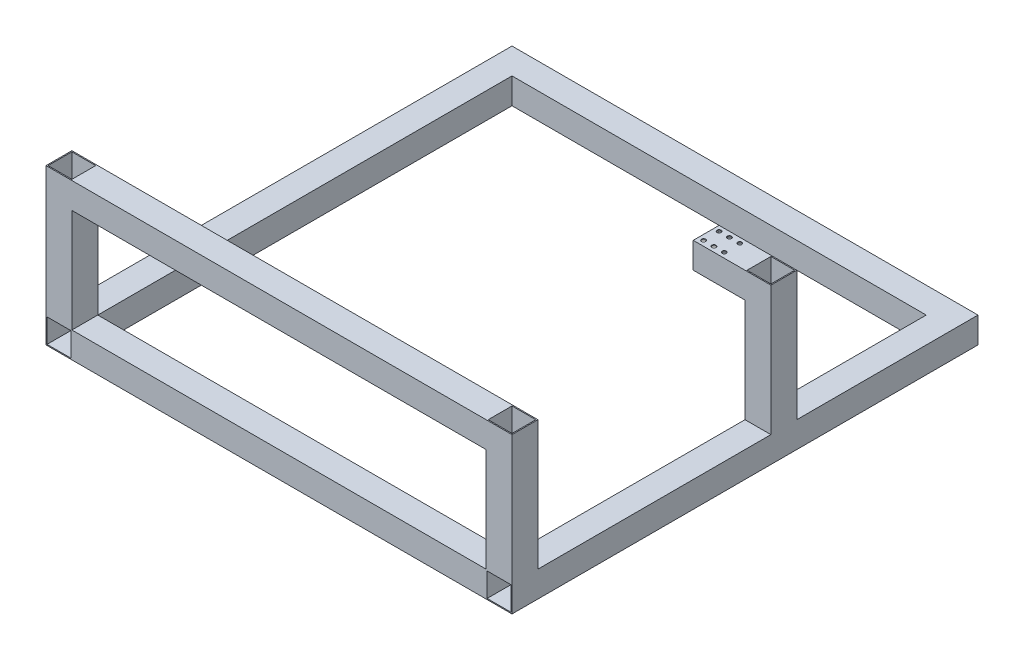
SolidWorks part; units mm, degrees
ref_plane "Front Plane" through (0, 0, 0) normal (0, 0, 1) x (1, 0, 0)
ref_plane "Top Plane" through (0, 0, 0) normal (0, 1, 0) x (1, 0, 0)
ref_plane "Right Plane" through (0, 0, 0) normal (1, 0, 0) x (0, 0, -1)
sketch "Sketch1" plane through (0, 0, 0) normal (0, 0, 1) x (1, 0, 0)
  line L0 (-11.5, 11.5) -> (-11.5, -11.5)
  line L1 (-12.5, 12.5) -> (12.5, 12.5)
  line L2 (-12.5, 12.5) -> (-12.5, -12.5)
  line L3 (-12.5, -12.5) -> (12.5, -12.5)
  line L4 (12.5, 12.5) -> (12.5, -12.5)
  line L5 (-12.5, 12.5) -> (12.5, -12.5) construction
  line L6 (-12.5, -12.5) -> (12.5, 12.5) construction
  line L7 (-11.5, -11.5) -> (11.5, -11.5)
  line L8 (11.5, 11.5) -> (11.5, -11.5)
  line L9 (-11.5, 11.5) -> (11.5, 11.5)
  point P0 (0, 0)
  dimension "D1" = 1
extrude "Boss-Extrude1" add sketch "Sketch1" along normal blind 450
sketch "Sketch2" plane through (12.5, 0, 0) normal (1, 0, 0) x (0, 0, -1)
  line L0 (-450, -12.5) -> (0, -12.5) construction
  line L1 (-450, 12.5) -> (-425, 12.5)
  line L2 (-450, 12.5) -> (-450, -12.5)
  line L3 (-450, -12.5) -> (-425, -12.5)
  line L4 (-425, 12.5) -> (-425, -12.5)
  line L5 (-450, 12.5) -> (-425, -12.5) construction
  line L6 (-450, -12.5) -> (-425, 12.5) construction
  line L7 (-450, -12.5) -> (-450, 12.5) construction
  line L9 (-449, 11.5) -> (-449, -11.5)
  line L10 (-449, -11.5) -> (-426, -11.5)
  line L11 (-426, 11.5) -> (-426, -11.5)
  line L12 (-449, 11.5) -> (-426, 11.5)
  point P0 (-437.5, 0)
  point P9 (-212.5, 0)
  dimension "D1" = 25
  dimension "D2" = 25
  dimension "D3" = 0
  dimension "D4" = 1
extrude "Boss-Extrude2" add sketch "Sketch2" along normal blind 200
sketch "Sketch3" plane through (12.5, 0, 0) normal (1, 0, 0) x (0, 0, -1)
  line L0 (-425, -12.5) -> (0, -12.5) construction
  line L1 (-25, 12.5) -> (0, 12.5)
  line L2 (-25, 12.5) -> (-25, -12.5)
  line L3 (-25, -12.5) -> (0, -12.5)
  line L4 (0, 12.5) -> (0, -12.5)
  line L5 (-25, 12.5) -> (0, -12.5) construction
  line L6 (-25, -12.5) -> (0, 12.5) construction
  line L7 (0, -12.5) -> (0, 12.5) construction
  line L8 (-24, 11.5) -> (-24, -11.5)
  line L9 (-24, -11.5) -> (-1, -11.5)
  line L10 (-1, 11.5) -> (-1, -11.5)
  line L11 (-24, 11.5) -> (-1, 11.5)
  point P0 (-12.5, 0)
  dimension "D1" = 25
  dimension "D2" = 25
  dimension "D3" = 0
  dimension "D4" = 1
extrude "Boss-Extrude3" add sketch "Sketch3" along normal blind 200
mirror "Mirror1" about plane through (212.5, 0, 0) normal (1, 0, 0) of "Boss-Extrude2", "Boss-Extrude3", "Boss-Extrude1"
sketch "Sketch4" plane through (0, 12.5, 0) normal (0, 1, 0) x (1, 0, 0)
  line L0 (437.5, -450) -> (437.5, 0) construction
  line L1 (412.5, -175) -> (437.5, -175)
  line L2 (412.5, -175) -> (412.5, -200)
  line L3 (412.5, -200) -> (437.5, -200)
  line L4 (437.5, -175) -> (437.5, -200)
  line L5 (412.5, -175) -> (437.5, -200) construction
  line L6 (412.5, -200) -> (437.5, -175) construction
  line L7 (437.5, -450) -> (-12.5, -450) construction
  line L8 (413.5, -176) -> (413.5, -199)
  line L9 (413.5, -199) -> (436.5, -199)
  line L10 (436.5, -176) -> (436.5, -199)
  line L11 (413.5, -176) -> (436.5, -176)
  point P0 (425, -187.5)
  dimension "D1" = 25
  dimension "D2" = 25
  dimension "D3" = 250
  dimension "D4" = 1
extrude "Boss-Extrude4" add sketch "Sketch4" along normal blind 125
sketch "Sketch5" plane through (412.5, 0, 0) normal (-1, 0, 0) x (0, 0, 1)
  line L0 (175, 137.5) -> (175, 12.5) construction
  line L1 (175, 137.5) -> (200, 137.5)
  line L2 (175, 137.5) -> (175, 112.5)
  line L3 (175, 112.5) -> (200, 112.5)
  line L4 (200, 137.5) -> (200, 112.5)
  line L5 (175, 137.5) -> (200, 112.5) construction
  line L6 (175, 112.5) -> (200, 137.5) construction
  line L7 (175, 137.5) -> (200, 137.5) construction
  line L8 (176, 136.5) -> (176, 113.5)
  line L9 (176, 113.5) -> (199, 113.5)
  line L10 (199, 136.5) -> (199, 113.5)
  line L11 (176, 136.5) -> (199, 136.5)
  point P0 (187.5, 125)
  point P5 (175, 125)
  dimension "D1" = 25
  dimension "D2" = 25
  dimension "D3" = 0
  dimension "D4" = 0
  dimension "D5" = 1
extrude "Boss-Extrude5" add sketch "Sketch5" along normal blind 50
sketch "Sketch6" plane through (0, 137.5, 0) normal (0, 1, 0) x (1, 0, 0)
  line L0 (362.5, -200) -> (362.5, -175) construction
  line L1 (437.5, -175) -> (362.5, -175) construction
  line L2 (362.5, -200) -> (437.5, -200) construction
  circle A0 centre (367.5, -180) radius 2
  circle A1 centre (367.5, -195) radius 2
  circle A2 centre (377.5, -180) radius 2
  circle A3 centre (377.5, -195) radius 2
  circle A4 centre (387.5, -180) radius 2
  circle A5 centre (387.5, -195) radius 2
  dimension "D1" = 5
  dimension "D2" = 10
  dimension "D3" = 10
  dimension "D4" = 5
  dimension "D5" = 10
  dimension "D6" = 10
  dimension "D7" = 5
  dimension "D8" = 5
  dimension "D9" = 5
  dimension "D10" = 5
  dimension "D11" = 5
  dimension "D12" = 5
extrude "Cut-Extrude1" cut sketch "Sketch6" against normal blind 25
sketch "Sketch7" plane through (0, 12.5, 0) normal (0, 1, 0) x (1, 0, 0)
  line L0 (437.5, -450) -> (437.5, -200) construction
  line L1 (412.5, -425) -> (437.5, -425)
  line L2 (412.5, -425) -> (412.5, -450)
  line L3 (412.5, -450) -> (437.5, -450)
  line L4 (437.5, -425) -> (437.5, -450)
  line L5 (412.5, -425) -> (437.5, -450) construction
  line L6 (412.5, -450) -> (437.5, -425) construction
  line L7 (437.5, -450) -> (-12.5, -450) construction
  line L8 (-12.5, -450) -> (-12.5, 0) construction
  line L9 (-12.5, -425) -> (12.5, -425)
  line L10 (-12.5, -425) -> (-12.5, -450)
  line L11 (-12.5, -450) -> (12.5, -450)
  line L12 (12.5, -425) -> (12.5, -450)
  line L13 (-12.5, -425) -> (12.5, -450) construction
  line L14 (-12.5, -450) -> (12.5, -425) construction
  line L15 (-11.5, -426) -> (-11.5, -449)
  line L16 (-11.5, -449) -> (11.5, -449)
  line L17 (11.5, -426) -> (11.5, -449)
  line L18 (-11.5, -426) -> (11.5, -426)
  line L20 (413.5, -426) -> (413.5, -449)
  line L21 (413.5, -449) -> (436.5, -449)
  line L22 (436.5, -426) -> (436.5, -449)
  line L23 (413.5, -426) -> (436.5, -426)
  point P0 (425, -437.5)
  point P9 (0, -437.5)
  dimension "D1" = 25
  dimension "D2" = 25
  dimension "D3" = 0
  dimension "D4" = 0
  dimension "D6" = 25
  dimension "D7" = 25
  dimension "D8" = 1
  dimension "D5" = 1
extrude "Boss-Extrude6" add sketch "Sketch7" along normal blind 125
sketch "Sketch8" plane through (412.5, 0, 0) normal (-1, 0, 0) x (0, 0, 1)
  line L0 (450, 137.5) -> (450, 12.5) construction
  line L1 (425, 137.5) -> (450, 137.5)
  line L2 (425, 137.5) -> (425, 112.5)
  line L3 (425, 112.5) -> (450, 112.5)
  line L4 (450, 137.5) -> (450, 112.5)
  line L5 (425, 137.5) -> (450, 112.5) construction
  line L6 (425, 112.5) -> (450, 137.5) construction
  line L7 (425, 137.5) -> (450, 137.5) construction
  line L8 (426, 136.5) -> (426, 113.5)
  line L9 (426, 113.5) -> (449, 113.5)
  line L10 (449, 136.5) -> (449, 113.5)
  line L11 (426, 136.5) -> (449, 136.5)
  point P0 (437.5, 125)
  dimension "D1" = 0
  dimension "D2" = 0
  dimension "D3" = 25
  dimension "D4" = 25
  dimension "D5" = 1
extrude "Boss-Extrude7" add sketch "Sketch8" along normal blind 400
